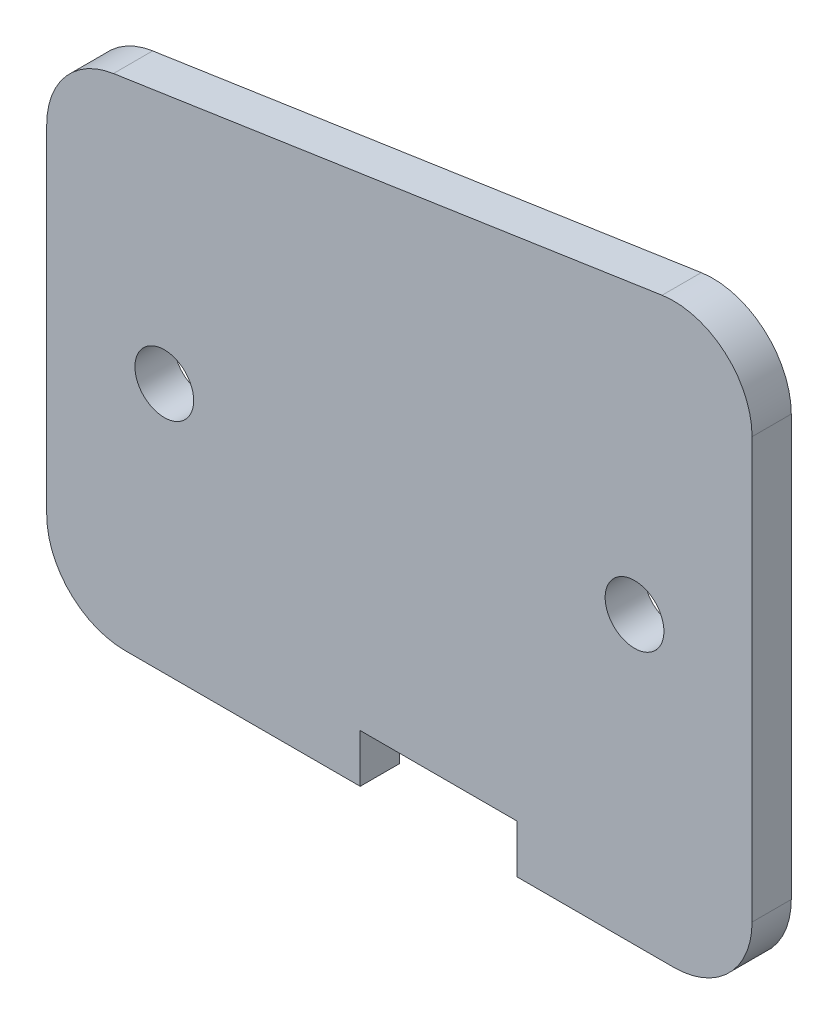
SolidWorks part; units mm, degrees
ref_plane "Front Plane" through (0, 0, 0) normal (0, 0, 1) x (1, 0, 0)
ref_plane "Top Plane" through (0, 0, 0) normal (0, 1, 0) x (1, 0, 0)
ref_plane "Right Plane" through (0, 0, 0) normal (1, 0, 0) x (0, 0, -1)
sketch "Sketch1" plane through (0, 0, 0) normal (0, 0, 1) x (1, 0, 0)
  line L6 (-114.3, 0) -> (-114.3, 46.355)
  line L7 (-152.4, 0) -> (-152.4, 40.64)
  line L13 (-104.775, 40.4102) -> (-104.775, 6.35)
  line L14 (-161.925, 6.35) -> (-161.925, 33.7427)
  line L15 (-156.517, 40.0225) -> (-112.067, 46.69)
  line L17 (-136.525, 0) -> (-136.525, 3.9159)
  line L18 (-136.525, 3.9159) -> (-123.825, 3.9159)
  line L19 (-123.825, 0) -> (-123.825, 3.9159)
  line L22 (-111.125, 0) -> (-123.825, 0)
  line L23 (-136.525, 0) -> (-155.575, 0)
  circle A0 centre (-152.4, 20.32) radius 2.3813
  circle A1 centre (-114.3, 23.1775) radius 2.3813
  arc A2 (-161.925, 6.35) -> (-155.575, 0) centre (-155.575, 6.35) ccw
  arc A3 (-104.775, 6.35) -> (-111.125, 0) centre (-111.125, 6.35) cw
  arc A4 (-104.775, 40.4102) -> (-112.067, 46.69) centre (-111.125, 40.4102) ccw
  arc A5 (-161.925, 33.7427) -> (-156.517, 40.0225) centre (-155.575, 33.7427) cw
  dimension "D9" = 4.7625
  dimension "D10" = 4.7625
  dimension "D2" = 6.35
  dimension "D6" = 9.525
  dimension "D7" = 38.1
  dimension "D8" = 9.525
  dimension "D11" = 12.7
  dimension "D12" = 9.525
extrude "Boss-Extrude1" add sketch "Sketch1" along normal blind 3.175 contours A5 L14 A2 L23 L7 A0 L15 | A1 L6 L15 L7 A0 L23 L17 L18 L19 L22 | L13 A4 L15 L6 A1 L22 A3
